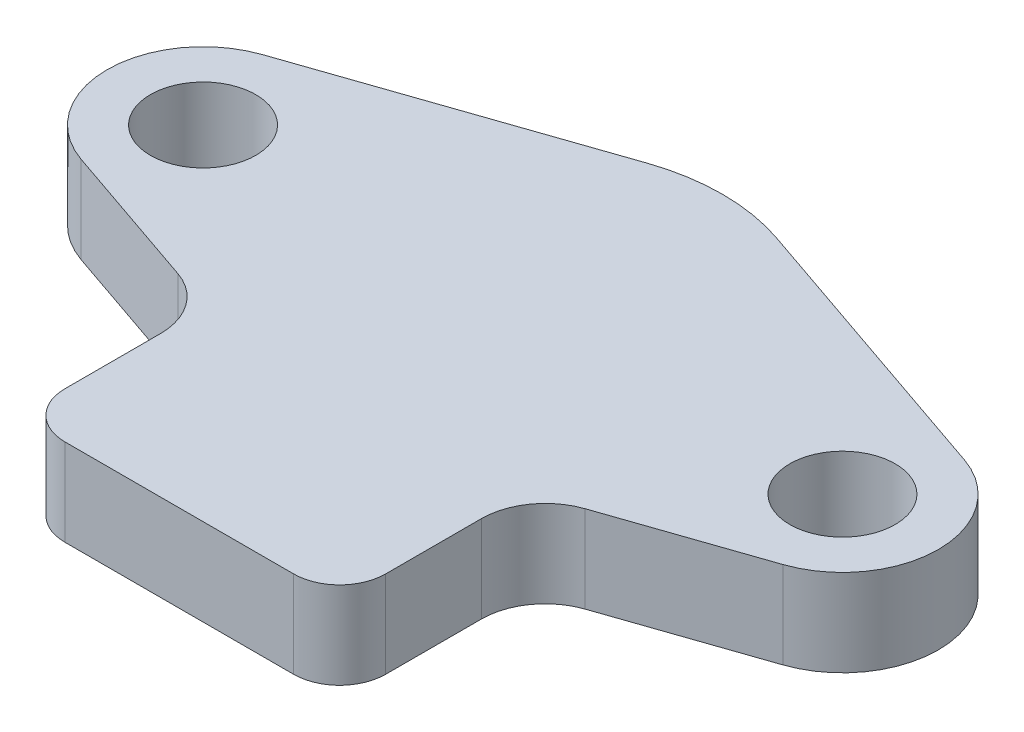
SolidWorks part; units mm, degrees
ref_plane "Front Plane" through (0, 0, 0) normal (0, 0, 1) x (1, 0, 0)
ref_plane "Top Plane" through (0, 0, 0) normal (0, 1, 0) x (1, 0, 0)
ref_plane "Right Plane" through (0, 0, 0) normal (1, 0, 0) x (0, 0, -1)
sketch "Sketch1" plane through (0, 0, 0) normal (0, 1, 0) x (1, 0, 0)
  line B0 (6.3754, -9.7536) -> (6.3754, -6.1404)
  line B1 (6.3754, -15.4686) -> (6.3754, -9.7536)
  line B2 (-5.6769, -17.0561) -> (5.6769, -17.0561)
  line B3 (7.9629, -14.7701) -> (7.9629, -10.0193)
  line B4 (10.1067, -7.0165) -> (17.4219, -4.5043)
  line B5 (17.4219, 4.5043) -> (3.2216, 9.3809)
  line B6 (-3.2216, 9.3809) -> (-17.4219, 4.5043)
  line B7 (-17.4219, -4.5043) -> (-10.1067, -7.0165)
  line B8 (-7.9629, -10.0193) -> (-7.9629, -14.7701)
  line B9 (-6.3754, -15.4686) -> (6.3754, -15.4686)
  line B10 (-6.3754, -6.1404) -> (-6.3754, -15.4686)
  line B11 (-6.3754, -6.1404) -> (-6.3754, -9.7536)
  arc B12 (15.875, -2.6162) -> (15.875, 2.6162) centre (15.875, 0) ccw
  arc B13 (5.6769, -17.0561) -> (7.9629, -14.7701) centre (5.6769, -14.7701) ccw
  arc B14 (10.1067, -7.0165) -> (7.9629, -10.0193) centre (11.1379, -10.0193) ccw
  arc B15 (17.4219, -4.5043) -> (17.4219, 4.5043) centre (15.875, 0) ccw
  arc B16 (3.2216, 9.3809) -> (0, 9.9187) centre (0, 0) ccw
  arc B17 (0, 9.9187) -> (-3.2216, 9.3809) centre (0, 0) ccw
  arc B18 (-17.4219, 4.5043) -> (-17.4219, -4.5043) centre (-15.875, 0) ccw
  arc B19 (-7.9629, -10.0193) -> (-10.1067, -7.0165) centre (-11.1379, -10.0193) ccw
  arc B20 (-7.9629, -14.7701) -> (-5.6769, -17.0561) centre (-5.6769, -14.7701) ccw
  arc B21 (15.875, 2.6162) -> (15.875, -2.6162) centre (15.875, 0) ccw
  arc B22 (6.7965, -4.8183) -> (6.3754, -6.1404) centre (8.6614, -6.1404) ccw
  arc B23 (-6.3754, -6.1404) -> (-6.7965, -4.8183) centre (-8.6614, -6.1404) ccw
  arc B24 (6.7965, -4.8183) -> (-6.7965, -4.8183) centre (0, 0) ccw
  arc B25 (-15.875, -2.6162) -> (-15.875, 2.6162) centre (-15.875, 0) ccw
  arc B26 (-15.875, 2.6162) -> (-15.875, -2.6162) centre (-15.875, 0) ccw
sketch_block_instance "Block-Sketch1-1"
sketch_block "Block-Sketch1"
extrude "Boss-Extrude1" add sketch "Sketch1" along normal blind 1.143 contours B8 B20 B2 B13 B3 B14 B4 B15 B5 B16 B17 B6 B18 B7 B19 B26 B25 B24 B22 B0 B1 B9 B10 B23 B21 B12
sketch "Sketch2" plane through (0, 1.143, 0) normal (0, 1, 0) x (1, 0, 0)
  line L7 (-7.9629, -10.0193) -> (-7.9629, -14.7701)
  line L8 (-5.6769, -17.0561) -> (5.6769, -17.0561)
  line L9 (7.9629, -14.7701) -> (7.9629, -10.0193)
  line L10 (10.1067, -7.0165) -> (17.4219, -4.5043)
  line L11 (17.4219, 4.5043) -> (3.2216, 9.3809)
  line L12 (-3.2216, 9.3809) -> (-17.4219, 4.5043)
  line L13 (-17.4219, -4.5043) -> (-10.1067, -7.0165)
  line L14 (-7.9629, -10.0193) -> (-7.9629, -14.7701)
  line L15 (-5.6769, -17.0561) -> (5.6769, -17.0561)
  line L16 (7.9629, -14.7701) -> (7.9629, -10.0193)
  line L17 (10.1067, -7.0165) -> (17.4219, -4.5043)
  line L18 (17.4219, 4.5043) -> (3.2216, 9.3809)
  line L19 (-3.2216, 9.3809) -> (-17.4219, 4.5043)
  line L20 (-17.4219, -4.5043) -> (-10.1067, -7.0165)
  circle A0 centre (15.875, 0) radius 2.6162 construction
  circle A1 centre (-15.875, 0) radius 2.6162 construction
  circle A2 centre (15.875, 0) radius 2.6162
  circle A3 centre (-15.875, 0) radius 2.6162
  arc A7 (-7.9629, -14.7701) -> (-5.6769, -17.0561) centre (-5.6769, -14.7701) ccw
  arc A8 (5.6769, -17.0561) -> (7.9629, -14.7701) centre (5.6769, -14.7701) ccw
  arc A9 (10.1067, -7.0165) -> (7.9629, -10.0193) centre (11.1379, -10.0193) ccw
  arc A10 (17.4219, -4.5043) -> (17.4219, 4.5043) centre (15.875, 0) ccw
  arc A11 (3.2216, 9.3809) -> (-3.2216, 9.3809) centre (0, 0) ccw
  arc A12 (-17.4219, 4.5043) -> (-17.4219, -4.5043) centre (-15.875, 0) ccw
  arc A13 (-7.9629, -10.0193) -> (-10.1067, -7.0165) centre (-11.1379, -10.0193) ccw
  arc A14 (-7.9629, -14.7701) -> (-5.6769, -17.0561) centre (-5.6769, -14.7701) ccw
  arc A15 (5.6769, -17.0561) -> (7.9629, -14.7701) centre (5.6769, -14.7701) ccw
  arc A16 (10.1067, -7.0165) -> (7.9629, -10.0193) centre (11.1379, -10.0193) ccw
  arc A17 (17.4219, -4.5043) -> (17.4219, 4.5043) centre (15.875, 0) ccw
  arc A18 (3.2216, 9.3809) -> (-3.2216, 9.3809) centre (0, 0) ccw
  arc A19 (-17.4219, 4.5043) -> (-17.4219, -4.5043) centre (-15.875, 0) ccw
  arc A20 (-7.9629, -10.0193) -> (-10.1067, -7.0165) centre (-11.1379, -10.0193) ccw
  dimension "D1" = 0
extrude "Boss-Extrude2" add sketch "Sketch2" along normal blind 3.175
